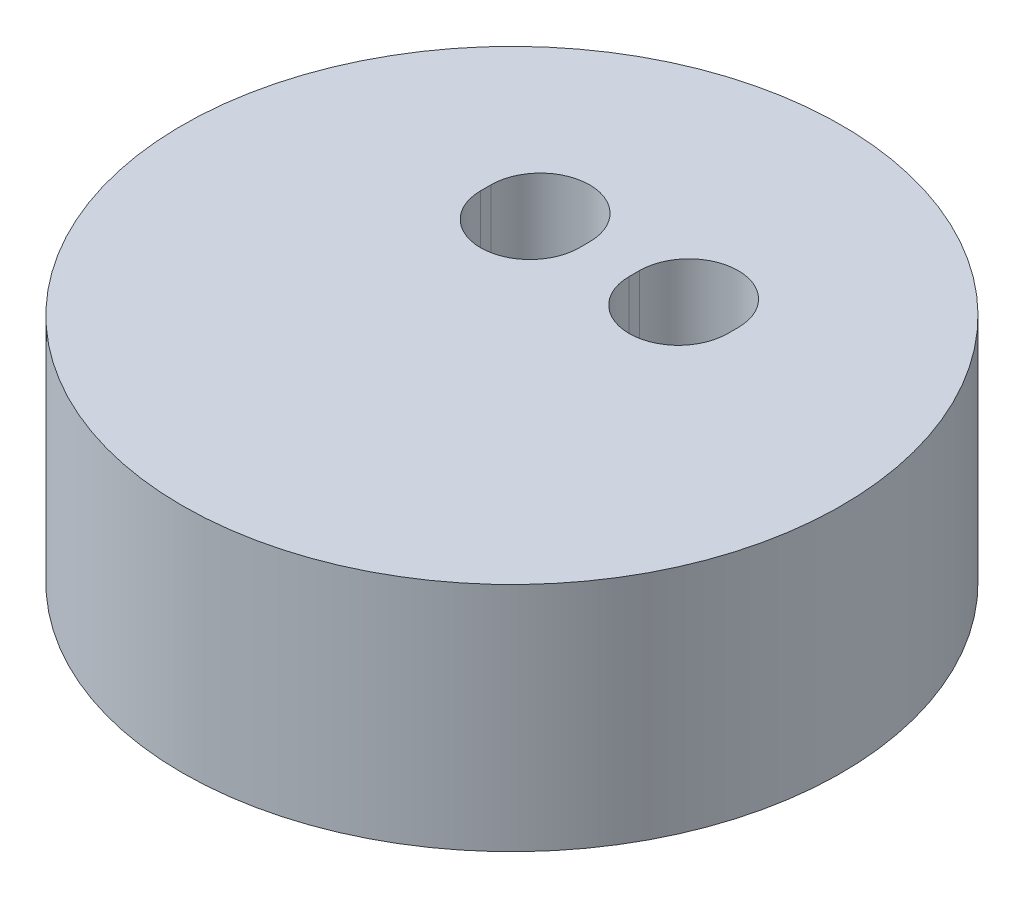
SolidWorks part; units mm, degrees
ref_plane "Front Plane" through (0, 0, 0) normal (0, 0, 1) x (1, 0, 0)
ref_plane "Top Plane" through (0, 0, 0) normal (0, 1, 0) x (1, 0, 0)
ref_plane "Right Plane" through (0, 0, 0) normal (1, 0, 0) x (0, 0, -1)
sketch "Sketch1" plane through (0, 0, 0) normal (0, 1, 0) x (1, 0, 0)
  circle A0 centre (0, 0) radius 12.36
  dimension "D1" = 24.72
extrude "Boss-Extrude1" add sketch "Sketch1" along normal blind 8.678
sketch "Sketch2" plane through (0, 8.678, 0) normal (0, 1, 0) x (1, 0, 0)
  line L0 (-2.785, 3.85) -> (-2.785, 3.46) construction
  line L1 (2.785, 3.85) -> (2.785, 3.46) construction
  line L2 (4.635, 3.85) -> (4.635, 3.46)
  line L3 (0.935, 3.85) -> (0.935, 3.46)
  line L4 (-0.935, 3.85) -> (-0.935, 3.46)
  line L5 (-4.635, 3.85) -> (-4.635, 3.46)
  line L6 (-2.785, 5.7) -> (2.785, 5.7) construction
  arc A3 (4.635, 3.85) -> (0.935, 3.85) centre (2.785, 3.85) ccw
  arc A4 (0.935, 3.46) -> (4.635, 3.46) centre (2.785, 3.46) ccw
  arc A5 (-0.935, 3.85) -> (-4.635, 3.85) centre (-2.785, 3.85) ccw
  arc A6 (-4.635, 3.46) -> (-0.935, 3.46) centre (-2.785, 3.46) ccw
  circle A7 centre (0, 0) radius 12.36 construction
  point P1 (-2.785, 3.655)
  point P2 (-4.635, 3.655)
  point P3 (-0.935, 3.655)
  point P8 (2.785, 3.655)
  point P14 (2.785, 5.7)
  point P15 (2.785, 1.61)
  point P16 (4.635, 3.655)
  point P17 (0.935, 3.655)
  point P20 (-2.785, 5.7)
  point P24 (-2.785, 1.61)
  point P29 (0, 5.7)
  dimension "D2" = 4.09
  dimension "D1" = 3.7
  dimension "D3" = 3.7
  dimension "D4" = 4.09
  dimension "D5" = 5.7
  dimension "D6" = 5.57
extrude "Cut-Extrude1" cut sketch "Sketch2" against normal through all
